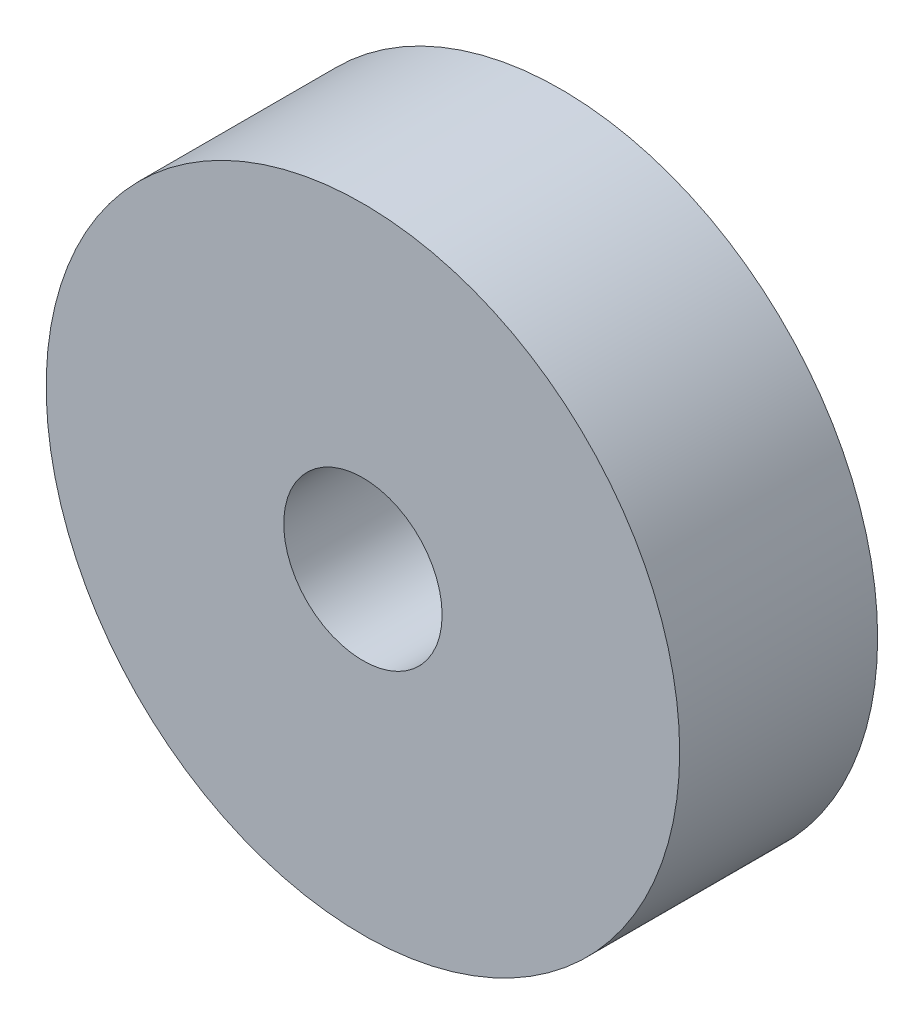
SolidWorks part; units mm, degrees
material "橡胶"
ref_plane "前视基准面" through (0, 0, 0) normal (0, 0, 1) x (1, 0, 0)
ref_plane "上视基准面" through (0, 0, 0) normal (0, 1, 0) x (1, 0, 0)
ref_plane "右视基准面" through (0, 0, 0) normal (1, 0, 0) x (0, 0, -1)
other "Configuration Table"
sketch "草图1" plane through (0, 0, 0) normal (0, 0, 1) x (1, 0, 0)
  circle A0 centre (0, 0) radius 2
  circle A1 centre (0, 0) radius 8
  dimension "D1" = 4
  dimension "D2" = 16
extrude "凸台-拉伸1" add sketch "草图1" along normal blind 5
